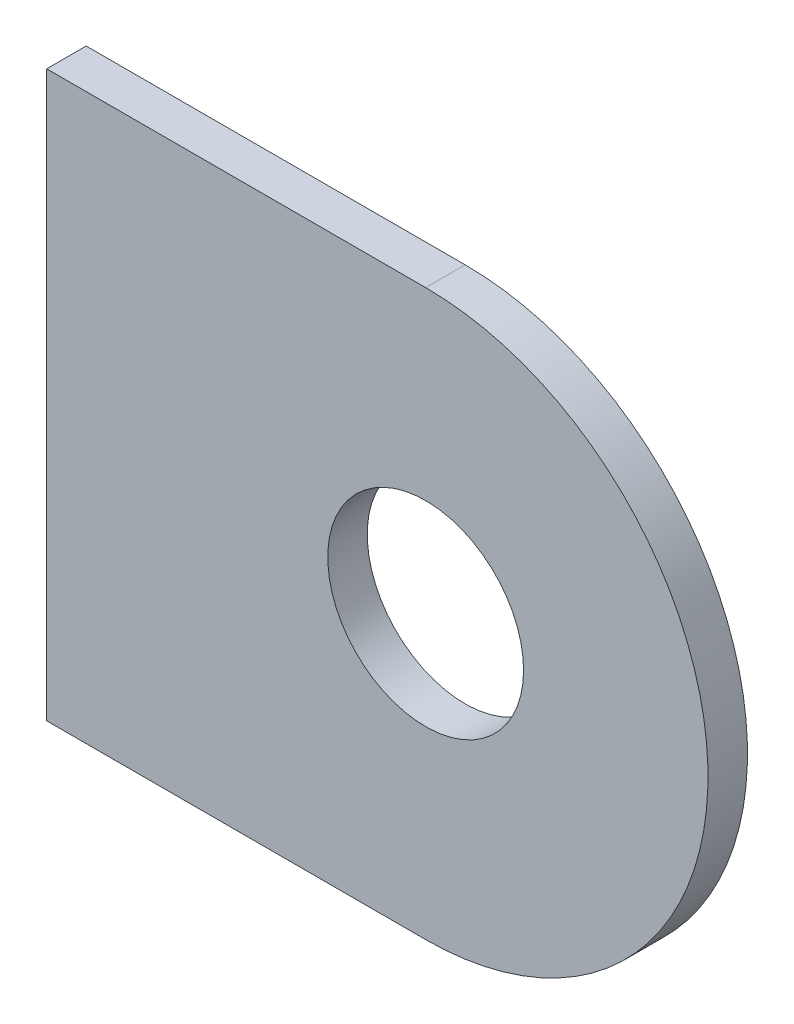
SolidWorks part; units mm, degrees
ref_plane "Front Plane" through (0, 0, 0) normal (0, 0, 1) x (1, 0, 0)
ref_plane "Top Plane" through (0, 0, 0) normal (0, 1, 0) x (1, 0, 0)
ref_plane "Right Plane" through (0, 0, 0) normal (1, 0, 0) x (0, 0, -1)
sketch "Sketch2" plane through (0, 0, 0) normal (0, 0, 1) x (1, 0, 0)
  line L1 (0, 0) -> (15.24, 0)
  line L2 (0, 0) -> (0, 22.7076)
  line L3 (0, 22.7076) -> (15.24, 22.7076)
  arc A0 (15.24, 0) -> (15.24, 22.7076) centre (15.24, 11.3538) ccw
  circle A1 centre (15.24, 11.3538) radius 3.937
  point P8 (0, 0)
  dimension "D3" = 7.874
  dimension "D1" = 15.24
  dimension "D2" = 22.7076
extrude "Boss-Extrude1" add sketch "Sketch2" along normal blind 1.5875
